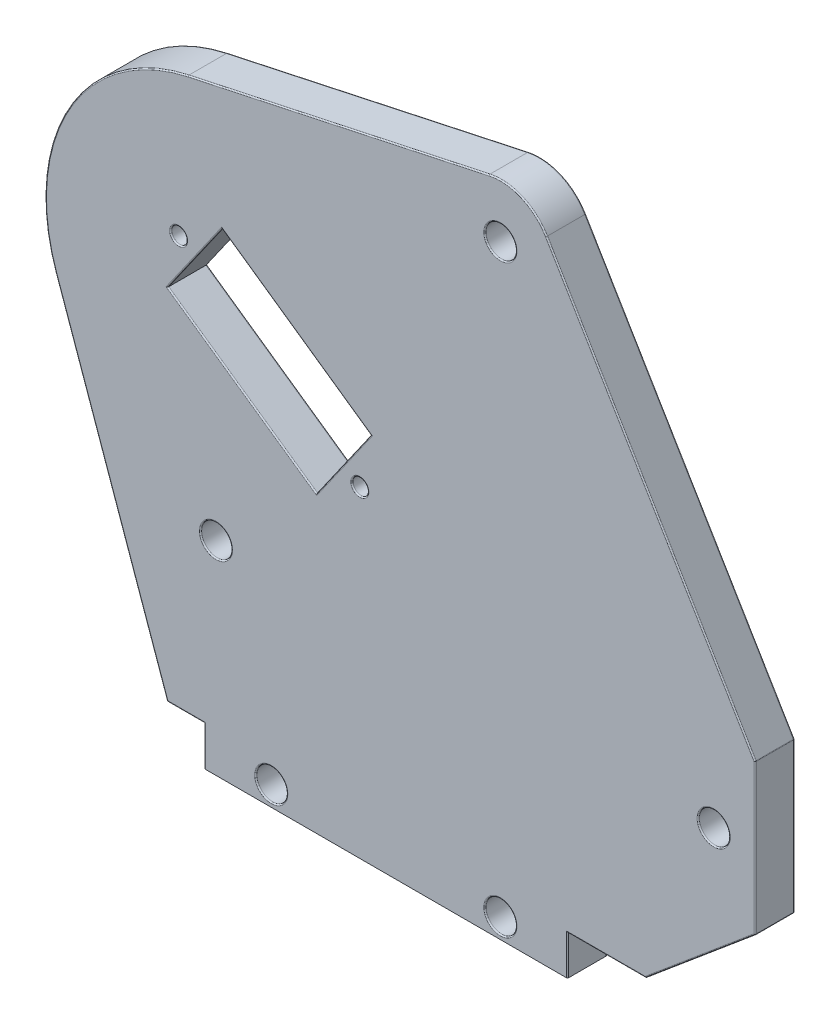
SolidWorks part; units mm, degrees
ref_plane "Front Plane" through (0, 0, 0) normal (0, 0, 1) x (1, 0, 0)
ref_plane "Top Plane" through (0, 0, 0) normal (0, 1, 0) x (1, 0, 0)
ref_plane "Right Plane" through (0, 0, 0) normal (1, 0, 0) x (0, 0, -1)
sketch "Sketch1" plane through (0, 0, 0) normal (0, 0, 1) x (1, 0, 0)
  line L0 (-23, 0) -> (-23, 10) construction
  line L1 (-23, 0) -> (23, 0) construction
  line L2 (23, 0) -> (23, 10) construction
  line L3 (23, 10) -> (32.896, 10) construction
  line L4 (32.896, 10) -> (46.746, 21.6215) construction
  line L5 (46.746, 21.6215) -> (46.746, 40.6215) construction
  line L6 (46.746, 40.6215) -> (20.3339, 84.9741) construction
  line L7 (-25.0297, 79.9436) -> (13.0723, 88.1382) construction
  line L8 (-27.6776, 10) -> (-41.7897, 49.9632) construction
  line L9 (-23, 10) -> (-27.6776, 10) construction
  line L10 (-23, 0) -> (-23, 10)
  line L11 (-23, 0) -> (23, 0)
  line L12 (23, 0) -> (23, 10)
  line L13 (23, 10) -> (32.896, 10)
  line L14 (32.896, 10) -> (46.746, 21.6215)
  line L15 (46.746, 21.6215) -> (46.746, 40.6215)
  line L16 (46.746, 40.6215) -> (20.3339, 84.9741)
  line L17 (-25.0297, 79.9436) -> (13.0723, 88.1382)
  line L18 (-27.6776, 10) -> (-41.7897, 49.9632)
  line L19 (-23, 10) -> (-27.6776, 10)
  line L20 (0, 0) -> (0, 11.2595) construction
  line L21 (-27.6191, 55.4363) -> (-20.7362, 65.2661)
  line L22 (-27.6191, 55.4363) -> (-8.7786, 42.244)
  line L23 (-20.7362, 65.2661) -> (-1.8957, 52.0738)
  line L24 (-8.7786, 42.244) -> (-1.8957, 52.0738)
  line L25 (-5.3371, 47.1589) -> (-24.1776, 60.3512) construction
  line L26 (-14.7574, 53.755) -> (-18.1989, 48.8401) construction
  arc A0 (20.3339, 84.9741) -> (13.0723, 88.1382) centre (14.5, 81.5) ccw construction
  arc A1 (-25.0297, 79.9436) -> (-41.7897, 49.9632) centre (-20.22, 57.58) ccw construction
  arc A2 (20.3339, 84.9741) -> (13.0723, 88.1382) centre (14.5, 81.5) ccw
  arc A3 (-25.0297, 79.9436) -> (-41.7897, 49.9632) centre (-20.22, 57.58) ccw
  circle A4 centre (-26.2255, 61.7851) radius 1
  circle A5 centre (-3.2893, 45.725) radius 1
  point P2 (-14.5, 7.5)
  point P4 (14.5, 7.5)
  point P6 (41.496, 30.7519)
  point P8 (-21.5, 30.7519)
  point P12 (14.5, 81.5)
  point P24 (-20.22, 57.58)
  dimension "D8" = 2
  dimension "D1" = 5.25
  dimension "D2" = 7.5
  dimension "D3" = 21.5
  dimension "D4" = 23
  dimension "D5" = 12
  dimension "D6" = 35
  dimension "D7" = 2.5
extrude "Boss-Extrude1" add sketch "Sketch1" along normal blind 5
hole_wizard "M3.5 Clearance Hole1" positions "Sketch4" profile "Sketch5" hole size "M3.5" standard "ISO" end condition through all
sketch "Sketch4" plane through (0, 0, 5) normal (0, 0, 1) x (1, 0, 0)
  point P0 (14.5, 81.5)
  point P3 (41.496, 30.7519)
  point P6 (14.5, 7.5)
  point P9 (-14.5, 7.5)
  point P12 (-21.5, 30.7519)
sketch "Sketch5" plane through (14.5, 81.5, 5) normal (1, 0, 0) x (0, -1, 0)
  line L0 (0, 0) -> (0, 5)
  line L1 (0, 5) -> (1.95, 5)
  line L2 (1.95, 5) -> (1.95, 0)
  line L5 (1.95, 0) -> (0, 0)
  line L11 (0, -6.35) -> (0, 107.95) construction
  dimension "Thru Hole Dia." = 3.9
  dimension "Thru Hole Depth" = 5
fillet "Fillet1" radius 0.15 52 edges at (16.45, 81.5, 5) (16.45, 81.5, 0) (43.446, 30.7519, 5) (43.446, 30.7519, 0) (16.45, 7.5, 5) (16.45, 7.5, 0) (-12.55, 7.5, 5) (-12.55, 7.5, 0) (-19.55, 30.7519, 5) (-19.55, 30.7519, 0) (-4.2893, 45.725, 0) (-4.2893, 45.725, 5) (-25.2255, 61.7851, 0) (-25.2255, 61.7851, 5) (-18.1989, 48.8401, 0) (-5.3371, 47.1589, 0) (-11.3159, 58.67, 0) (-24.1776, 60.3512, 0) (-18.1989, 48.8401, 5) (-5.3371, 47.1589, 5) (-11.3159, 58.67, 5) (-24.1776, 60.3512, 5) (0, 0, 0) (23, 5, 0) (27.948, 10, 0) (39.821, 15.8108, 0) (46.746, 31.1215, 0) (33.54, 62.7978, 0) (17.2123, 87.7247, 0) (-5.9787, 84.0409, 0) (-40.1868, 68.742, 0) (-34.7336, 29.9816, 0) (-25.3388, 10, 0) (-23, 5, 0) (0, 0, 5) (23, 5, 5) (27.948, 10, 5) (39.821, 15.8108, 5) (46.746, 31.1215, 5) (33.54, 62.7978, 5) (17.2123, 87.7247, 5) (-5.9787, 84.0409, 5) (-40.1868, 68.742, 5) (-34.7336, 29.9816, 5) (-25.3388, 10, 5) (-23, 5, 5) (-23, 0, 2.5) (-27.6776, 10, 2.5) (46.746, 40.6215, 2.5) (46.746, 21.6215, 2.5) (32.896, 10, 2.5) (23, 0, 2.5)
sketch "Sketch6" plane through (0, 0, 0) normal (0, 0, 1) x (1, 0, 0)
  line L0 (23, 0) -> (23, 10) construction
  line L1 (-23, 0) -> (23, 0)
  line L2 (-23, 0) -> (-23, 5)
  line L3 (-23, 5) -> (23, 5)
  line L4 (23, 0) -> (23, 5)
  dimension "D1" = 5
extrude "Cut-Extrude1" cut sketch "Sketch6" along normal through all contours L2 L1 L4 L3
